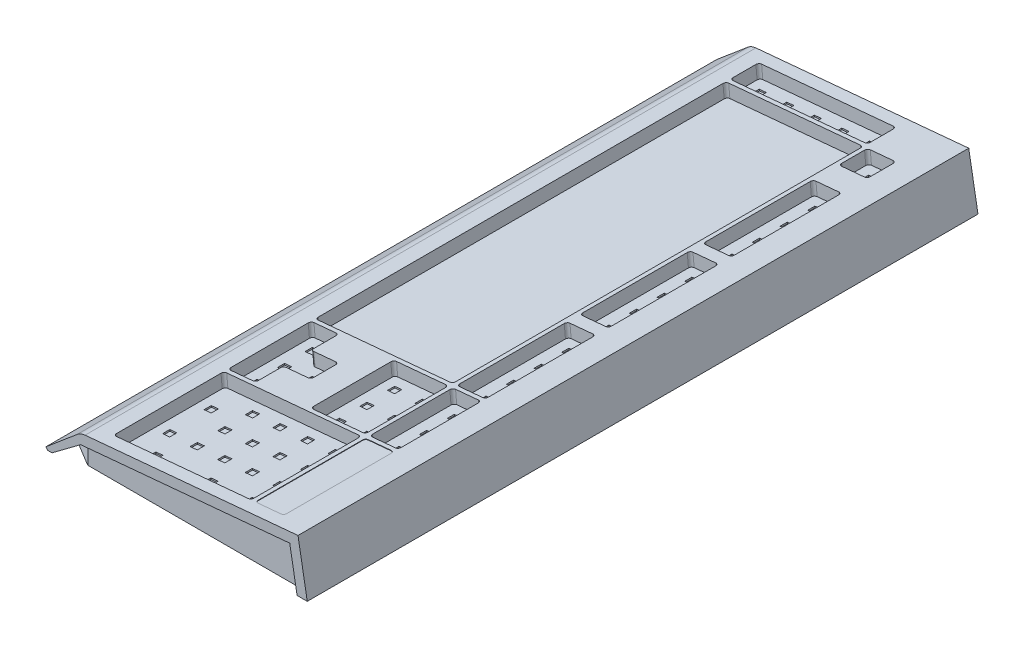
SolidWorks part; units mm, degrees
ref_plane "Front Plane" through (0, 0, 0) normal (0, 0, 1) x (1, 0, 0)
ref_plane "Top Plane" through (0, 0, 0) normal (0, 1, 0) x (1, 0, 0)
ref_plane "Right Plane" through (0, 0, 0) normal (1, 0, 0) x (0, 0, -1)
sketch "Sketch1" plane through (0, 0, 0) normal (0, 0, 1) x (1, 0, 0)
  line L0 (-76, 22) -> (76, 36)
  line L1 (-76, 0) -> (76, 0)
  line L2 (-76, 0) -> (-76, 22)
  line L4 (76, 0) -> (76, 36)
  point P2 (0, 29)
  dimension "D1" = 36
  dimension "D2" = 22
  dimension "D3" = 0
  dimension "D4" = 152
  dimension "D5" = 0
extrude "Boss-Extrude1" add sketch "Sketch1" along normal blind 459
sketch "Sketch4" plane through (0, 0, 459) normal (0, 0, 1) x (1, 0, 0)
  line L1 (70.2253, 28.4385) -> (75.3604, -0.684)
  line L2 (70.2253, 28.4385) -> (-76, 14.9704)
  line L3 (-76, 22) -> (-76, 0) construction
  line L4 (76, 36) -> (-76, 22) construction
  line L7 (76, 36) -> (-76, 22)
  line L8 (-76, 22) -> (-76, 14.9704)
  line L10 (76, 36) -> (82.4684, -0.684)
  line L11 (82.4684, -0.684) -> (75.3604, -0.684)
  dimension "D1" = 7
  dimension "D2" = 80
  dimension "D3" = 7
extrude "Boss-Extrude3" add sketch "Sketch4" along normal blind 5
sketch "Sketch6" plane through (0, 0, 0) normal (0, 0, -1) x (-1, 0, 0)
  line L0 (-69, 0) -> (-69, 28.3256)
  line L1 (76, 0) -> (-76, 0) construction
  line L2 (-69, 28.3256) -> (76, 14.9704)
  line L3 (76, 22) -> (76, 0) construction
  line L4 (76, 14.9704) -> (76, 22)
  line L5 (76, 22) -> (-76, 36)
  line L6 (-76, 36) -> (-76, 0)
  line L7 (-76, 0) -> (-69, 0)
  dimension "D1" = 7
  dimension "D2" = 7
extrude "Boss-Extrude5" add sketch "Sketch6" along normal blind 5
sketch "Sketch10" plane through (0, 0, 459) normal (0, 0, 1) x (1, 0, 0)
  line L0 (-76, 0) -> (-96, 0)
  line L1 (-96, 0) -> (-76, 14.9704)
  line L2 (-76, 14.9704) -> (-76, 0)
  dimension "D1" = 20
extrude "Boss-Extrude6" add sketch "Sketch10" against normal up to surface (459 mm away) up to face at (-3.5, 10.824, 0)
sketch "Sketch11" plane through (0, 0, 0) normal (0, -1, 0) x (1, 0, 0)
  line L0 (-76, -2.5) -> (-76, 461.5) construction
  line L1 (-76, -5) -> (-76, 0) construction
  line L2 (-76, 464) -> (-76, 459) construction
  line L3 (-76, 459) -> (-96, 447)
  line L4 (-96, 0) -> (-96, 459) construction
  line L5 (-96, 447) -> (-96, 459)
  line L6 (-96, 459) -> (-76, 459)
  line L7 (-76, 0) -> (-96, 12)
  line L9 (-96, 12) -> (-96, 0)
  line L10 (-96, 0) -> (-76, 0)
  dimension "D1" = 12
  dimension "D2" = 12
extrude "Cut-Extrude3" cut sketch "Sketch11" against normal up to next
sketch "Sketch12" plane through (0, 0, 464) normal (0, 0, 1) x (1, 0, 0)
  line L0 (-76, 14.9704) -> (-96, 0)
  line L1 (-96, 0) -> (-99, 0)
  line L2 (-99, 0) -> (-100.2034, 1.6077)
  line L3 (-100.2034, 1.6077) -> (-76, 22)
  line L4 (-76, 22) -> (-76, 14.9704)
  dimension "D1" = 3
  dimension "D2" = 3.3
extrude "Boss-Extrude7" add sketch "Sketch12" against normal up to surface (469 mm away) up to face at (23, 16.8827, -5)
sketch "Sketch19" plane through (0, 0, 459) normal (0, 0, -1) x (-1, 0, 0)
  line L3 (-82.4684, -0.684) -> (-75.3604, -0.684)
  line L4 (-76, 0) -> (-76, 36)
  line L5 (-76, 36) -> (-82.4684, -0.684)
  line L6 (-82.4684, -0.684) -> (-75.3604, -0.684)
  line L7 (-76, 0) -> (-76, 36)
  line L8 (-76, 36) -> (-82.4684, -0.684)
  line L11 (-75.3604, -0.684) -> (-75.2398, 0)
  line L12 (-75.3604, -0.684) -> (-75.2398, 0)
  line L13 (-75.2398, 0) -> (-76, 0)
  line L14 (-75.2398, 0) -> (-76, 0)
  dimension "D1" = 0
extrude "Boss-Extrude8" add sketch "Sketch19" along normal up to surface (464 mm away) up to face at (-17.467, 11.4337, -5)
sketch "Sketch20" plane through (0, 0, -5) normal (0, 0, -1) x (-1, 0, 0)
  line L0 (-69, 28.3256) -> (-73.9946, 0)
  line L2 (-76, 36) -> (-82.4684, -0.684) construction
  line L3 (-69, 28.3256) -> (-69, 0)
  line L4 (-75.2398, 0) -> (-69, 0) construction
  line L5 (-69, 0) -> (-69, 28.3256) construction
  line L6 (-69, 0) -> (-73.9946, 0)
extrude "Cut-Extrude10" cut sketch "Sketch20" against normal up to surface (5 mm away) up to face at (-3.5, 10.824, 0)
sketch "Sketch22" plane through (-2.6486, 28.7561, 0) normal (-0.0917, 0.9958, 0) x (0.9958, 0.0917, 0)
  line L0 (78.9815, -464) -> (-73.6619, -464) construction
  line L1 (57.9815, -378) -> (41.9815, -378)
  line L2 (59.9815, -380) -> (59.9815, -453)
  line L3 (57.9815, -455) -> (41.9815, -455)
  line L4 (39.9815, -380) -> (39.9815, -453)
  line L6 (78.9815, -464) -> (78.9815, 5) construction
  arc A0 (41.9815, -378) -> (39.9815, -380) centre (41.9815, -380) ccw
  arc A1 (41.9815, -455) -> (39.9815, -453) centre (41.9815, -453) cw
  arc A2 (59.9815, -453) -> (57.9815, -455) centre (57.9815, -453) cw
  arc A3 (57.9815, -378) -> (59.9815, -380) centre (57.9815, -380) cw
  point P10 (39.9815, -455)
  point P13 (59.9815, -455)
  point P16 (59.9815, -378)
  dimension "D4" = 2
  dimension "D1" = 9
  dimension "D2" = 77
  dimension "D3" = 20
  dimension "D5" = 19
extrude "Cut-Extrude12" cut sketch "Sketch22" against normal blind 0.3
sketch "Sketch23" plane through (-2.6486, 28.7561, 0) normal (-0.0917, 0.9958, 0) x (0.9958, 0.0917, 0)
  line L0 (78.9815, -464) -> (-73.6619, -464) construction
  line L2 (36.9815, -380) -> (36.9815, -453)
  line L3 (34.9815, -455) -> (-57.4385, -455)
  line L5 (39.9815, -380) -> (39.9815, -453) construction
  line L12 (-59.4385, -453) -> (-59.4385, -380)
  line L13 (-57.4385, -378) -> (34.9815, -378)
  line L14 (57.9815, -375) -> (41.9815, -375)
  line L15 (39.9815, -373) -> (39.9815, -319)
  line L16 (41.9815, -317) -> (57.9815, -317)
  line L17 (59.9815, -319) -> (59.9815, -373)
  line L19 (59.9815, -453) -> (59.9815, -380) construction
  line L20 (34.9815, -375) -> (0.5515, -375)
  line L21 (-59.4385, -373) -> (-59.4385, -319)
  line L22 (-57.4385, -317) -> (-42.1085, -317)
  line L23 (36.9815, -319) -> (36.9815, -373)
  line L24 (-40.1085, -319) -> (-40.1085, -334.3333)
  line L25 (-1.4485, -319) -> (-1.4485, -373)
  line L26 (-20.7785, -338.3333) -> (-20.7785, -353.6667)
  line L27 (0.5515, -317) -> (34.9815, -317)
  line L28 (-42.1085, -375) -> (-57.4385, -375)
  line L29 (-22.7785, -336.3333) -> (-38.1085, -336.3333)
  line L30 (-22.7785, -355.6667) -> (-38.1085, -355.6667)
  line L31 (-40.1085, -357.6667) -> (-40.1085, -373)
  line L36 (39.9815, -373) -> (39.9815, 5) construction
  line L37 (-73.6619, 5) -> (78.9815, 5) construction
  line L38 (59.9815, -319) -> (59.9815, 5) construction
  line L39 (57.9815, -314) -> (41.9815, -314)
  line L40 (39.9815, -312) -> (39.9815, -239)
  line L41 (41.9815, -237) -> (57.9815, -237)
  line L42 (59.9815, -239) -> (59.9815, -312)
  line L43 (57.9815, -228) -> (41.9815, -228)
  line L44 (39.9815, -226) -> (39.9815, -153)
  line L45 (41.9815, -151) -> (57.9815, -151)
  line L46 (59.9815, -153) -> (59.9815, -226)
  line L47 (57.9815, -142) -> (41.9815, -142)
  line L48 (39.9815, -140) -> (39.9815, -67)
  line L49 (41.9815, -65) -> (57.9815, -65)
  line L50 (59.9815, -67) -> (59.9815, -140)
  line L51 (57.9815, -27) -> (41.9815, -27)
  line L52 (39.9815, -29) -> (39.9815, -45)
  line L53 (41.9815, -47) -> (57.9815, -47)
  line L54 (59.9815, -45) -> (59.9815, -29)
  line L55 (36.9815, -319) -> (36.9815, 5) construction
  line L56 (-59.4385, -319) -> (-59.4385, 5) construction
  line L57 (34.9815, -4) -> (-57.4385, -4)
  line L58 (-59.4385, -6) -> (-59.4385, -22)
  line L59 (-57.4385, -24) -> (34.9815, -24)
  line L60 (36.9815, -22) -> (36.9815, -6)
  line L61 (34.9815, -27) -> (-57.4385, -27)
  line L62 (-59.4385, -29) -> (-59.4385, -312)
  line L63 (-57.4385, -314) -> (34.9815, -314)
  line L64 (36.9815, -312) -> (36.9815, -29)
  arc A4 (-59.4385, -380) -> (-57.4385, -378) centre (-57.4385, -380) cw
  arc A5 (-57.4385, -455) -> (-59.4385, -453) centre (-57.4385, -453) cw
  arc A6 (36.9815, -453) -> (34.9815, -455) centre (34.9815, -453) cw
  arc A7 (36.9815, -380) -> (34.9815, -378) centre (34.9815, -380) ccw
  arc A8 (39.9815, -319) -> (41.9815, -317) centre (41.9815, -319) cw
  arc A9 (41.9815, -375) -> (39.9815, -373) centre (41.9815, -373) cw
  arc A10 (57.9815, -375) -> (59.9815, -373) centre (57.9815, -373) ccw
  arc A11 (57.9815, -317) -> (59.9815, -319) centre (57.9815, -319) cw
  arc A12 (-40.1085, -373) -> (-42.1085, -375) centre (-42.1085, -373) cw
  arc A13 (-57.4385, -375) -> (-59.4385, -373) centre (-57.4385, -373) cw
  arc A14 (-59.4385, -319) -> (-57.4385, -317) centre (-57.4385, -319) cw
  arc A15 (-40.1085, -319) -> (-42.1085, -317) centre (-42.1085, -319) ccw
  arc A16 (-38.1085, -336.3333) -> (-40.1085, -334.3333) centre (-38.1085, -334.3333) cw
  arc A17 (-38.1085, -355.6667) -> (-40.1085, -357.6667) centre (-38.1085, -357.6667) ccw
  arc A18 (-22.7785, -355.6667) -> (-20.7785, -353.6667) centre (-22.7785, -353.6667) ccw
  arc A19 (-22.7785, -336.3333) -> (-20.7785, -338.3333) centre (-22.7785, -338.3333) cw
  arc A20 (-1.4485, -319) -> (0.5515, -317) centre (0.5515, -319) cw
  arc A21 (-1.4485, -373) -> (0.5515, -375) centre (0.5515, -373) ccw
  arc A22 (34.9815, -375) -> (36.9815, -373) centre (34.9815, -373) ccw
  arc A23 (34.9815, -317) -> (36.9815, -319) centre (34.9815, -319) cw
  arc A24 (57.9815, -314) -> (59.9815, -312) centre (57.9815, -312) ccw
  arc A25 (41.9815, -314) -> (39.9815, -312) centre (41.9815, -312) cw
  arc A26 (39.9815, -239) -> (41.9815, -237) centre (41.9815, -239) cw
  arc A27 (57.9815, -237) -> (59.9815, -239) centre (57.9815, -239) cw
  arc A28 (57.9815, -228) -> (59.9815, -226) centre (57.9815, -226) ccw
  arc A29 (41.9815, -228) -> (39.9815, -226) centre (41.9815, -226) cw
  arc A30 (39.9815, -153) -> (41.9815, -151) centre (41.9815, -153) cw
  arc A31 (57.9815, -151) -> (59.9815, -153) centre (57.9815, -153) cw
  arc A32 (39.9815, -67) -> (41.9815, -65) centre (41.9815, -67) cw
  arc A33 (41.9815, -142) -> (39.9815, -140) centre (41.9815, -140) cw
  arc A34 (57.9815, -142) -> (59.9815, -140) centre (57.9815, -140) ccw
  arc A35 (57.9815, -65) -> (59.9815, -67) centre (57.9815, -67) cw
  arc A36 (41.9815, -27) -> (39.9815, -29) centre (41.9815, -29) ccw
  arc A37 (39.9815, -45) -> (41.9815, -47) centre (41.9815, -45) ccw
  arc A38 (57.9815, -47) -> (59.9815, -45) centre (57.9815, -45) ccw
  arc A39 (57.9815, -27) -> (59.9815, -29) centre (57.9815, -29) cw
  arc A40 (-57.4385, -4) -> (-59.4385, -6) centre (-57.4385, -6) ccw
  arc A41 (-59.4385, -22) -> (-57.4385, -24) centre (-57.4385, -22) ccw
  arc A42 (34.9815, -24) -> (36.9815, -22) centre (34.9815, -22) ccw
  arc A43 (34.9815, -4) -> (36.9815, -6) centre (34.9815, -6) cw
  arc A44 (-57.4385, -27) -> (-59.4385, -29) centre (-57.4385, -29) ccw
  arc A45 (-59.4385, -312) -> (-57.4385, -314) centre (-57.4385, -312) ccw
  arc A46 (34.9815, -314) -> (36.9815, -312) centre (34.9815, -312) ccw
  arc A47 (34.9815, -27) -> (36.9815, -29) centre (34.9815, -29) cw
  point P11 (-59.4385, -455)
  point P15 (36.9815, -455)
  point P16 (36.9815, -455)
  point P49 (-40.1085, -375)
  point P60 (-40.1085, -355.6667)
  point P67 (-1.4485, -317)
  point P92 (59.9815, -314)
  point P95 (39.9815, -314)
  point P98 (39.9815, -237)
  point P101 (59.9815, -237)
  point P104 (59.9815, -228)
  point P107 (39.9815, -228)
  point P110 (39.9815, -151)
  point P113 (59.9815, -151)
  point P116 (39.9815, -65)
  point P119 (39.9815, -142)
  point P122 (59.9815, -142)
  point P125 (59.9815, -65)
  point P132 (39.9815, -27)
  point P135 (39.9815, -47)
  point P138 (59.9815, -47)
  point P141 (59.9815, -27)
  point P150 (-59.4385, -4)
  point P153 (-59.4385, -24)
  point P156 (36.9815, -24)
  point P159 (36.9815, -4)
  point P166 (-59.4385, -27)
  point P169 (-59.4385, -314)
  point P172 (36.9815, -314)
  point P175 (36.9815, -27)
  dimension "D5" = 2
  dimension "D10" = 2
  dimension "D18" = 2
  dimension "D25" = 2
  dimension "D28" = 2
  dimension "D31" = 2
  dimension "D34" = 2
  dimension "D3" = 77
  dimension "D4" = 3
  dimension "D6" = 3
  dimension "D7" = 58
  dimension "D8" = 0
  dimension "D9" = 20
  dimension "D11" = 3
  dimension "D12" = 96.42
  dimension "D13" = 38.43
  dimension "D14" = 19.33
  dimension "D15" = 19.33
  dimension "D16" = 19.3333
  dimension "D17" = 19.3333
  dimension "D19" = 3
  dimension "D20" = 77
  dimension "D21" = 9
  dimension "D22" = 77
  dimension "D23" = 9
  dimension "D24" = 77
  dimension "D26" = 18
  dimension "D27" = 20
  dimension "D29" = 3
  dimension "D30" = 20
  dimension "D32" = 3
  dimension "D33" = 3
  dimension "D35" = 9
  dimension "D36" = 96.42
extrude "Cut-Extrude13" cut sketch "Sketch23" against normal blind 9
fillet "Fillet5" radius 10 1 edges at (-76, 22, 229.5)
sketch "Sketch78" plane through (-1.8231, 19.794, 0) normal (-0.0917, 0.9958, 0) x (0.9958, 0.0917, 0)
  line L0 (-20.7785, -346) -> (-59.4385, -346) construction
  line L1 (-20.7785, -353.6667) -> (-20.7785, -338.3333) construction
  line L2 (-59.4385, -319) -> (-59.4385, -373) construction
  line L3 (-49.7735, -317) -> (-49.7735, -375) construction
  line L4 (-42.1085, -317) -> (-57.4385, -317) construction
  line L5 (-57.4385, -375) -> (-42.1085, -375) construction
  line L6 (-40.1085, -326.6667) -> (-59.4385, -326.6667) construction
  line L7 (-40.1085, -334.3333) -> (-40.1085, -319) construction
  line L8 (-40.1085, -365.3333) -> (-59.4385, -365.3333) construction
  line L9 (-40.1085, -373) -> (-40.1085, -357.6667) construction
  line L10 (-30.4435, -336.3333) -> (-30.4435, -355.6667) construction
  line L11 (-22.7785, -336.3333) -> (-38.1085, -336.3333) construction
  line L12 (-38.1085, -355.6667) -> (-22.7785, -355.6667) construction
  line L13 (36.9815, -346) -> (-1.4485, -346) construction
  line L14 (-32.9435, -348.5) -> (-27.9435, -348.5)
  line L15 (-32.9435, -348.5) -> (-32.9435, -343.5)
  line L16 (-32.9435, -343.5) -> (-27.9435, -343.5)
  line L17 (-27.9435, -348.5) -> (-27.9435, -343.5)
  line L18 (-32.9435, -348.5) -> (-27.9435, -343.5) construction
  line L19 (-32.9435, -343.5) -> (-27.9435, -348.5) construction
  line L20 (-52.2735, -329.1667) -> (-47.2735, -329.1667)
  line L21 (-52.2735, -329.1667) -> (-52.2735, -324.1667)
  line L22 (-52.2735, -324.1667) -> (-47.2735, -324.1667)
  line L23 (-47.2735, -329.1667) -> (-47.2735, -324.1667)
  line L24 (-52.2735, -329.1667) -> (-47.2735, -324.1667) construction
  line L25 (-52.2735, -324.1667) -> (-47.2735, -329.1667) construction
  line L26 (-52.2735, -348.5) -> (-47.2735, -348.5)
  line L27 (-52.2735, -348.5) -> (-52.2735, -343.5)
  line L28 (-52.2735, -343.5) -> (-47.2735, -343.5)
  line L29 (-47.2735, -348.5) -> (-47.2735, -343.5)
  line L30 (-52.2735, -348.5) -> (-47.2735, -343.5) construction
  line L31 (-52.2735, -343.5) -> (-47.2735, -348.5) construction
  line L32 (-52.2735, -367.8333) -> (-47.2735, -367.8333)
  line L33 (-52.2735, -367.8333) -> (-52.2735, -362.8333)
  line L34 (-52.2735, -362.8333) -> (-47.2735, -362.8333)
  line L35 (-47.2735, -367.8333) -> (-47.2735, -362.8333)
  line L36 (-52.2735, -367.8333) -> (-47.2735, -362.8333) construction
  line L37 (-52.2735, -362.8333) -> (-47.2735, -367.8333) construction
  line L38 (36.9815, -373) -> (36.9815, -319) construction
  line L39 (-1.4485, -319) -> (-1.4485, -373) construction
  line L40 (36.9815, -326.6667) -> (-1.4485, -326.6667) construction
  line L41 (36.9815, -365.3333) -> (-1.4485, -365.3333) construction
  line L42 (-59.4385, -380) -> (-59.4385, -453) construction
  line L43 (34.9815, -317) -> (0.5515, -317) construction
  line L44 (0.5515, -375) -> (34.9815, -375) construction
  line L45 (49.9815, -317) -> (49.9815, -375) construction
  line L46 (57.9815, -317) -> (41.9815, -317) construction
  line L47 (27.4315, -317) -> (27.4315, -375) construction
  line L48 (8.1015, -317) -> (8.1015, -375) construction
  line L49 (41.9815, -375) -> (57.9815, -375) construction
  line L50 (24.9315, -348.5) -> (29.9315, -348.5)
  line L51 (24.9315, -348.5) -> (24.9315, -343.5)
  line L52 (24.9315, -343.5) -> (29.9315, -343.5)
  line L53 (29.9315, -348.5) -> (29.9315, -343.5)
  line L54 (24.9315, -348.5) -> (29.9315, -343.5) construction
  line L55 (24.9315, -343.5) -> (29.9315, -348.5) construction
  line L56 (5.6015, -348.5) -> (10.6015, -348.5)
  line L57 (5.6015, -348.5) -> (5.6015, -343.5)
  line L58 (5.6015, -343.5) -> (10.6015, -343.5)
  line L59 (10.6015, -348.5) -> (10.6015, -343.5)
  line L60 (5.6015, -348.5) -> (10.6015, -343.5) construction
  line L61 (5.6015, -343.5) -> (10.6015, -348.5) construction
  line L62 (24.9315, -367.8333) -> (29.9315, -367.8333)
  line L63 (24.9315, -367.8333) -> (24.9315, -362.8333)
  line L64 (24.9315, -362.8333) -> (29.9315, -362.8333)
  line L65 (29.9315, -367.8333) -> (29.9315, -362.8333)
  line L66 (24.9315, -367.8333) -> (29.9315, -362.8333) construction
  line L67 (24.9315, -362.8333) -> (29.9315, -367.8333) construction
  line L68 (24.9315, -329.1667) -> (29.9315, -329.1667)
  line L69 (24.9315, -329.1667) -> (24.9315, -324.1667)
  line L70 (24.9315, -324.1667) -> (29.9315, -324.1667)
  line L71 (29.9315, -329.1667) -> (29.9315, -324.1667)
  line L72 (24.9315, -329.1667) -> (29.9315, -324.1667) construction
  line L73 (24.9315, -324.1667) -> (29.9315, -329.1667) construction
  line L74 (5.6015, -329.1667) -> (10.6015, -329.1667)
  line L75 (5.6015, -329.1667) -> (5.6015, -324.1667)
  line L76 (5.6015, -324.1667) -> (10.6015, -324.1667)
  line L77 (10.6015, -329.1667) -> (10.6015, -324.1667)
  line L78 (5.6015, -329.1667) -> (10.6015, -324.1667) construction
  line L79 (5.6015, -324.1667) -> (10.6015, -329.1667) construction
  line L80 (5.6015, -367.8333) -> (10.6015, -367.8333)
  line L81 (5.6015, -367.8333) -> (5.6015, -362.8333)
  line L82 (5.6015, -362.8333) -> (10.6015, -362.8333)
  line L83 (10.6015, -367.8333) -> (10.6015, -362.8333)
  line L84 (5.6015, -367.8333) -> (10.6015, -362.8333) construction
  line L85 (5.6015, -362.8333) -> (10.6015, -367.8333) construction
  line L86 (59.9815, -346) -> (39.9815, -346) construction
  line L87 (59.9815, -373) -> (59.9815, -319) construction
  line L88 (39.9815, -319) -> (39.9815, -373) construction
  line L89 (59.9815, -326.6667) -> (39.9815, -326.6667) construction
  line L90 (59.9815, -365.3333) -> (39.9815, -365.3333) construction
  line L91 (59.9815, -37) -> (39.9815, -37) construction
  line L92 (47.4815, -329.1667) -> (52.4815, -329.1667)
  line L93 (47.4815, -329.1667) -> (47.4815, -324.1667)
  line L94 (47.4815, -324.1667) -> (52.4815, -324.1667)
  line L95 (52.4815, -329.1667) -> (52.4815, -324.1667)
  line L96 (47.4815, -329.1667) -> (52.4815, -324.1667) construction
  line L97 (47.4815, -324.1667) -> (52.4815, -329.1667) construction
  line L98 (47.4815, -348.5) -> (52.4815, -348.5)
  line L99 (47.4815, -348.5) -> (47.4815, -343.5)
  line L100 (47.4815, -343.5) -> (52.4815, -343.5)
  line L101 (52.4815, -348.5) -> (52.4815, -343.5)
  line L102 (47.4815, -348.5) -> (52.4815, -343.5) construction
  line L103 (47.4815, -343.5) -> (52.4815, -348.5) construction
  line L104 (47.4815, -367.8333) -> (52.4815, -367.8333)
  line L105 (47.4815, -367.8333) -> (47.4815, -362.8333)
  line L106 (47.4815, -362.8333) -> (52.4815, -362.8333)
  line L107 (52.4815, -367.8333) -> (52.4815, -362.8333)
  line L108 (47.4815, -367.8333) -> (52.4815, -362.8333) construction
  line L109 (47.4815, -362.8333) -> (52.4815, -367.8333) construction
  line L110 (59.9815, -45) -> (59.9815, -29) construction
  line L111 (39.9815, -29) -> (39.9815, -45) construction
  line L112 (49.9815, -27) -> (49.9815, -47) construction
  line L113 (57.9815, -27) -> (41.9815, -27) construction
  line L114 (41.9815, -47) -> (57.9815, -47) construction
  line L115 (36.9815, -14) -> (-59.4385, -14) construction
  line L116 (47.4815, -39.5) -> (52.4815, -39.5)
  line L117 (47.4815, -39.5) -> (47.4815, -34.5)
  line L118 (47.4815, -34.5) -> (52.4815, -34.5)
  line L119 (52.4815, -39.5) -> (52.4815, -34.5)
  line L120 (47.4815, -39.5) -> (52.4815, -34.5) construction
  line L121 (47.4815, -34.5) -> (52.4815, -39.5) construction
  line L122 (36.9815, -22) -> (36.9815, -6) construction
  line L123 (-59.4385, -6) -> (-59.4385, -22) construction
  line L124 (-11.2285, -4) -> (-11.2285, -24) construction
  line L125 (34.9815, -4) -> (-57.4385, -4) construction
  line L126 (-57.4385, -24) -> (34.9815, -24) construction
  line L127 (27.4315, -4) -> (27.4315, -24) construction
  line L128 (8.1015, -4) -> (8.1015, -24) construction
  line L129 (-30.5585, -4) -> (-30.5585, -24) construction
  line L130 (-49.8885, -4) -> (-49.8885, -24) construction
  line L131 (49.9815, -65) -> (49.9815, -314) construction
  line L132 (24.9315, -16.5) -> (29.9315, -16.5)
  line L133 (24.9315, -16.5) -> (24.9315, -11.5)
  line L134 (24.9315, -11.5) -> (29.9315, -11.5)
  line L135 (29.9315, -16.5) -> (29.9315, -11.5)
  line L136 (24.9315, -16.5) -> (29.9315, -11.5) construction
  line L137 (24.9315, -11.5) -> (29.9315, -16.5) construction
  line L138 (5.6015, -16.5) -> (10.6015, -16.5)
  line L139 (5.6015, -16.5) -> (5.6015, -11.5)
  line L140 (5.6015, -11.5) -> (10.6015, -11.5)
  line L141 (10.6015, -16.5) -> (10.6015, -11.5)
  line L142 (5.6015, -16.5) -> (10.6015, -11.5) construction
  line L143 (5.6015, -11.5) -> (10.6015, -16.5) construction
  line L144 (-13.7285, -16.5) -> (-8.7285, -16.5)
  line L145 (-13.7285, -16.5) -> (-13.7285, -11.5)
  line L146 (-13.7285, -11.5) -> (-8.7285, -11.5)
  line L147 (-8.7285, -16.5) -> (-8.7285, -11.5)
  line L148 (-13.7285, -16.5) -> (-8.7285, -11.5) construction
  line L149 (-13.7285, -11.5) -> (-8.7285, -16.5) construction
  line L150 (-33.0585, -16.5) -> (-28.0585, -16.5)
  line L151 (-33.0585, -16.5) -> (-33.0585, -11.5)
  line L152 (-33.0585, -11.5) -> (-28.0585, -11.5)
  line L153 (-28.0585, -16.5) -> (-28.0585, -11.5)
  line L154 (-33.0585, -16.5) -> (-28.0585, -11.5) construction
  line L155 (-33.0585, -11.5) -> (-28.0585, -16.5) construction
  line L156 (-52.3885, -16.5) -> (-47.3885, -16.5)
  line L157 (-52.3885, -16.5) -> (-52.3885, -11.5)
  line L158 (-52.3885, -11.5) -> (-47.3885, -11.5)
  line L159 (-47.3885, -16.5) -> (-47.3885, -11.5)
  line L160 (-52.3885, -16.5) -> (-47.3885, -11.5) construction
  line L161 (-52.3885, -11.5) -> (-47.3885, -16.5) construction
  line L162 (57.9815, -65) -> (41.9815, -65) construction
  line L163 (41.9815, -314) -> (57.9815, -314) construction
  line L164 (59.9815, -74.505) -> (39.9815, -74.505) construction
  line L165 (59.9815, -140) -> (59.9815, -67) construction
  line L166 (39.9815, -67) -> (39.9815, -140) construction
  line L167 (59.9815, -93.835) -> (39.9815, -93.835) construction
  line L168 (59.9815, -113.165) -> (39.9815, -113.165) construction
  line L169 (59.9815, -132.495) -> (39.9815, -132.495) construction
  line L170 (-1.5635, -455) -> (-1.5635, -378) construction
  line L171 (-13.7285, -428.67) -> (-8.7285, -428.67)
  line L172 (-13.7285, -428.67) -> (-13.7285, -423.67)
  line L173 (-13.7285, -423.67) -> (-8.7285, -423.67)
  line L174 (-8.7285, -428.67) -> (-8.7285, -423.67)
  line L175 (69.2142, -146.5) -> (26.7315, -146.5) construction
  line L176 (47.4815, -72.005) -> (52.4815, -72.005)
  line L177 (47.4815, -72.005) -> (47.4815, -77.005)
  line L178 (47.4815, -77.005) -> (52.4815, -77.005)
  line L179 (52.4815, -72.005) -> (52.4815, -77.005)
  line L180 (47.4815, -72.005) -> (52.4815, -77.005) construction
  line L181 (47.4815, -77.005) -> (52.4815, -72.005) construction
  line L182 (47.4815, -91.335) -> (52.4815, -91.335)
  line L183 (47.4815, -91.335) -> (47.4815, -96.335)
  line L184 (47.4815, -96.335) -> (52.4815, -96.335)
  line L185 (52.4815, -91.335) -> (52.4815, -96.335)
  line L186 (47.4815, -91.335) -> (52.4815, -96.335) construction
  line L187 (47.4815, -96.335) -> (52.4815, -91.335) construction
  line L188 (47.4815, -110.665) -> (52.4815, -110.665)
  line L189 (47.4815, -110.665) -> (47.4815, -115.665)
  line L190 (47.4815, -115.665) -> (52.4815, -115.665)
  line L191 (52.4815, -110.665) -> (52.4815, -115.665)
  line L192 (47.4815, -110.665) -> (52.4815, -115.665) construction
  line L193 (47.4815, -115.665) -> (52.4815, -110.665) construction
  line L194 (47.4815, -129.995) -> (52.4815, -129.995)
  line L195 (47.4815, -129.995) -> (47.4815, -134.995)
  line L196 (47.4815, -134.995) -> (52.4815, -134.995)
  line L197 (52.4815, -129.995) -> (52.4815, -134.995)
  line L198 (47.4815, -129.995) -> (52.4815, -134.995) construction
  line L199 (47.4815, -134.995) -> (52.4815, -129.995) construction
  line L200 (67.6137, -232.5) -> (26.7315, -232.5) construction
  line L201 (41.9815, -228) -> (57.9815, -228) construction
  line L202 (-13.7285, -428.67) -> (-8.7285, -423.67) construction
  line L203 (-13.7285, -423.67) -> (-8.7285, -428.67) construction
  line L204 (41.9815, -142) -> (57.9815, -142) construction
  line L205 (52.4815, -163.005) -> (52.4815, -158.005)
  line L206 (47.4815, -158.005) -> (52.4815, -158.005)
  line L207 (47.4815, -163.005) -> (47.4815, -158.005)
  line L208 (47.4815, -163.005) -> (52.4815, -163.005)
  line L209 (52.4815, -182.335) -> (52.4815, -177.335)
  line L210 (47.4815, -177.335) -> (52.4815, -177.335)
  line L211 (47.4815, -182.335) -> (47.4815, -177.335)
  line L212 (47.4815, -182.335) -> (52.4815, -182.335)
  line L213 (47.4815, -196.665) -> (52.4815, -196.665)
  line L214 (47.4815, -201.665) -> (47.4815, -196.665)
  line L215 (47.4815, -201.665) -> (52.4815, -201.665)
  line L216 (52.4815, -201.665) -> (52.4815, -196.665)
  line L217 (52.4815, -220.995) -> (52.4815, -215.995)
  line L218 (47.4815, -220.995) -> (52.4815, -220.995)
  line L219 (47.4815, -220.995) -> (47.4815, -215.995)
  line L220 (47.4815, -215.995) -> (52.4815, -215.995)
  line L221 (47.4815, -244.005) -> (52.4815, -244.005)
  line L222 (47.4815, -244.005) -> (47.4815, -249.005)
  line L223 (47.4815, -249.005) -> (52.4815, -249.005)
  line L224 (52.4815, -244.005) -> (52.4815, -249.005)
  line L225 (47.4815, -263.335) -> (47.4815, -268.335)
  line L226 (47.4815, -263.335) -> (52.4815, -263.335)
  line L227 (52.4815, -263.335) -> (52.4815, -268.335)
  line L228 (47.4815, -268.335) -> (52.4815, -268.335)
  line L229 (47.4815, -282.665) -> (52.4815, -282.665)
  line L230 (47.4815, -282.665) -> (47.4815, -287.665)
  line L231 (47.4815, -287.665) -> (52.4815, -287.665)
  line L232 (52.4815, -282.665) -> (52.4815, -287.665)
  line L233 (47.4815, -301.995) -> (52.4815, -301.995)
  line L234 (47.4815, -301.995) -> (47.4815, -306.995)
  line L235 (47.4815, -306.995) -> (52.4815, -306.995)
  line L236 (52.4815, -301.995) -> (52.4815, -306.995)
  line L237 (27.4315, -455) -> (27.4315, -378) construction
  line L238 (-57.4385, -455) -> (34.9815, -455) construction
  line L239 (34.9815, -378) -> (-57.4385, -378) construction
  line L240 (8.1015, -455) -> (8.1015, -378) construction
  line L241 (-11.2285, -455) -> (-11.2285, -378) construction
  line L242 (-30.5585, -455) -> (-30.5585, -378) construction
  line L243 (-49.8885, -455) -> (-49.8885, -378) construction
  line L244 (36.9815, -387.51) -> (-59.4385, -387.51) construction
  line L245 (-13.7285, -409.34) -> (-8.7285, -409.34)
  line L246 (-13.7285, -409.34) -> (-13.7285, -404.34)
  line L247 (-13.7285, -404.34) -> (-8.7285, -404.34)
  line L248 (-8.7285, -409.34) -> (-8.7285, -404.34)
  line L249 (36.9815, -453) -> (36.9815, -380) construction
  line L250 (36.9815, -406.84) -> (-59.4385, -406.84) construction
  line L251 (36.9815, -426.17) -> (-59.4385, -426.17) construction
  line L252 (36.9815, -445.5) -> (-59.4385, -445.5) construction
  line L253 (-13.7285, -409.34) -> (-8.7285, -404.34) construction
  line L254 (24.9315, -390.01) -> (29.9315, -390.01)
  line L255 (24.9315, -390.01) -> (24.9315, -385.01)
  line L256 (24.9315, -385.01) -> (29.9315, -385.01)
  line L257 (29.9315, -390.01) -> (29.9315, -385.01)
  line L258 (24.9315, -390.01) -> (29.9315, -385.01) construction
  line L259 (24.9315, -385.01) -> (29.9315, -390.01) construction
  line L260 (24.9315, -409.34) -> (29.9315, -409.34)
  line L261 (24.9315, -409.34) -> (24.9315, -404.34)
  line L262 (24.9315, -404.34) -> (29.9315, -404.34)
  line L263 (29.9315, -409.34) -> (29.9315, -404.34)
  line L264 (24.9315, -409.34) -> (29.9315, -404.34) construction
  line L265 (24.9315, -404.34) -> (29.9315, -409.34) construction
  line L266 (24.9315, -428.67) -> (29.9315, -428.67)
  line L267 (24.9315, -428.67) -> (24.9315, -423.67)
  line L268 (24.9315, -423.67) -> (29.9315, -423.67)
  line L269 (29.9315, -428.67) -> (29.9315, -423.67)
  line L270 (24.9315, -428.67) -> (29.9315, -423.67) construction
  line L271 (24.9315, -423.67) -> (29.9315, -428.67) construction
  line L272 (24.9315, -448) -> (29.9315, -448)
  line L273 (24.9315, -448) -> (24.9315, -443)
  line L274 (24.9315, -443) -> (29.9315, -443)
  line L275 (29.9315, -448) -> (29.9315, -443)
  line L276 (24.9315, -448) -> (29.9315, -443) construction
  line L277 (24.9315, -443) -> (29.9315, -448) construction
  line L278 (-13.7285, -404.34) -> (-8.7285, -409.34) construction
  line L279 (-13.7285, -390.01) -> (-8.7285, -390.01)
  line L280 (-13.7285, -390.01) -> (-13.7285, -385.01)
  line L281 (-13.7285, -385.01) -> (-8.7285, -385.01)
  line L282 (-8.7285, -390.01) -> (-8.7285, -385.01)
  line L283 (-13.7285, -390.01) -> (-8.7285, -385.01) construction
  line L284 (-13.7285, -385.01) -> (-8.7285, -390.01) construction
  line L285 (5.6015, -390.01) -> (10.6015, -390.01)
  line L286 (5.6015, -390.01) -> (5.6015, -385.01)
  line L287 (5.6015, -385.01) -> (10.6015, -385.01)
  line L288 (10.6015, -390.01) -> (10.6015, -385.01)
  line L289 (5.6015, -390.01) -> (10.6015, -385.01) construction
  line L290 (5.6015, -385.01) -> (10.6015, -390.01) construction
  line L291 (5.6015, -409.34) -> (10.6015, -409.34)
  line L292 (5.6015, -409.34) -> (5.6015, -404.34)
  line L293 (5.6015, -404.34) -> (10.6015, -404.34)
  line L294 (10.6015, -409.34) -> (10.6015, -404.34)
  line L295 (5.6015, -409.34) -> (10.6015, -404.34) construction
  line L296 (5.6015, -404.34) -> (10.6015, -409.34) construction
  line L297 (5.6015, -428.67) -> (10.6015, -428.67)
  line L298 (5.6015, -428.67) -> (5.6015, -423.67)
  line L299 (5.6015, -423.67) -> (10.6015, -423.67)
  line L300 (10.6015, -428.67) -> (10.6015, -423.67)
  line L301 (5.6015, -428.67) -> (10.6015, -423.67) construction
  line L302 (5.6015, -423.67) -> (10.6015, -428.67) construction
  line L303 (-40.2235, -378) -> (-40.2235, -455) construction
  line L304 (0.9365, -448) -> (-4.0635, -448)
  line L305 (0.9365, -448) -> (0.9365, -443)
  line L306 (0.9365, -443) -> (-4.0635, -443)
  line L307 (-4.0635, -448) -> (-4.0635, -443)
  line L308 (0.9365, -448) -> (-4.0635, -443) construction
  line L309 (0.9365, -443) -> (-4.0635, -448) construction
  line L310 (-33.0585, -390.01) -> (-28.0585, -390.01)
  line L311 (-33.0585, -390.01) -> (-33.0585, -385.01)
  line L312 (-33.0585, -385.01) -> (-28.0585, -385.01)
  line L313 (-28.0585, -390.01) -> (-28.0585, -385.01)
  line L314 (-33.0585, -390.01) -> (-28.0585, -385.01) construction
  line L315 (-33.0585, -385.01) -> (-28.0585, -390.01) construction
  line L316 (-33.0585, -409.34) -> (-28.0585, -409.34)
  line L317 (-33.0585, -409.34) -> (-33.0585, -404.34)
  line L318 (-33.0585, -404.34) -> (-28.0585, -404.34)
  line L319 (-28.0585, -409.34) -> (-28.0585, -404.34)
  line L320 (-33.0585, -409.34) -> (-28.0585, -404.34) construction
  line L321 (-33.0585, -404.34) -> (-28.0585, -409.34) construction
  line L322 (-33.0585, -428.67) -> (-28.0585, -428.67)
  line L323 (-33.0585, -428.67) -> (-33.0585, -423.67)
  line L324 (-33.0585, -423.67) -> (-28.0585, -423.67)
  line L325 (-28.0585, -428.67) -> (-28.0585, -423.67)
  line L326 (-33.0585, -428.67) -> (-28.0585, -423.67) construction
  line L327 (-33.0585, -423.67) -> (-28.0585, -428.67) construction
  line L328 (-30.5585, -397.175) -> (-59.4385, -397.175) construction
  line L329 (-42.7235, -448) -> (-37.7235, -448)
  line L330 (-42.7235, -448) -> (-42.7235, -443)
  line L331 (-42.7235, -443) -> (-37.7235, -443)
  line L332 (-37.7235, -448) -> (-37.7235, -443)
  line L333 (-42.7235, -448) -> (-37.7235, -443) construction
  line L334 (-42.7235, -443) -> (-37.7235, -448) construction
  line L335 (-52.3885, -428.67) -> (-47.3885, -428.67)
  line L336 (-52.3885, -428.67) -> (-52.3885, -423.67)
  line L337 (-52.3885, -423.67) -> (-47.3885, -423.67)
  line L338 (-47.3885, -428.67) -> (-47.3885, -423.67)
  line L339 (-52.3885, -428.67) -> (-47.3885, -423.67) construction
  line L340 (-52.3885, -423.67) -> (-47.3885, -428.67) construction
  line L341 (-52.3885, -399.675) -> (-47.3885, -399.675)
  line L342 (-52.3885, -399.675) -> (-52.3885, -394.675)
  line L343 (-52.3885, -394.675) -> (-47.3885, -394.675)
  line L344 (-47.3885, -399.675) -> (-47.3885, -394.675)
  line L345 (-52.3885, -399.675) -> (-47.3885, -394.675) construction
  line L346 (-52.3885, -394.675) -> (-47.3885, -399.675) construction
  point P26 (-30.4435, -346)
  point P31 (-49.7735, -326.6667)
  point P36 (-49.7735, -346)
  point P41 (-49.7735, -365.3333)
  point P66 (27.4315, -346)
  point P71 (8.1015, -346)
  point P76 (27.4315, -365.3333)
  point P81 (27.4315, -326.6667)
  point P86 (8.1015, -326.6667)
  point P91 (8.1015, -365.3333)
  point P112 (49.9815, -326.6667)
  point P117 (49.9815, -346)
  point P122 (49.9815, -365.3333)
  point P139 (49.9815, -37)
  point P164 (27.4315, -14)
  point P169 (8.1015, -14)
  point P174 (-11.2285, -14)
  point P179 (-30.5585, -14)
  point P184 (-49.8885, -14)
  point P207 (49.9815, -93.835)
  point P209 (49.9815, -74.505)
  point P217 (49.9815, -113.165)
  point P222 (49.9815, -132.495)
  point P289 (27.4315, -406.84)
  point P293 (27.4315, -387.51)
  point P299 (27.4315, -426.17)
  point P304 (27.4315, -445.5)
  point P309 (-11.2285, -406.84)
  point P316 (-11.2285, -387.51)
  point P321 (-11.2285, -426.17)
  point P326 (8.1015, -387.51)
  point P331 (8.1015, -406.84)
  point P336 (8.1015, -426.17)
  point P341 (-1.5635, -445.5)
  point P346 (-30.5585, -406.84)
  point P349 (-30.5585, -387.51)
  point P358 (-30.5585, -426.17)
  point P365 (-40.2235, -445.5)
  point P370 (-49.8885, -397.175)
  point P374 (-49.8885, -426.17)
  point P380 (-49.8885, -401.3007)
  dimension "D1" = 5
  dimension "D2" = 5
  dimension "D3" = 5
  dimension "D4" = 5
  dimension "D5" = 5
  dimension "D6" = 5
  dimension "D7" = 5
  dimension "D8" = 5
  dimension "D9" = 9.55
  dimension "D10" = 19.33
  dimension "D11" = 5
  dimension "D12" = 5
  dimension "D13" = 5
  dimension "D14" = 5
  dimension "D15" = 5
  dimension "D16" = 5
  dimension "D17" = 5
  dimension "D18" = 5
  dimension "D19" = 5
  dimension "D20" = 5
  dimension "D21" = 5
  dimension "D22" = 5
  dimension "D23" = 5
  dimension "D24" = 5
  dimension "D25" = 5
  dimension "D26" = 5
  dimension "D27" = 5
  dimension "D28" = 5
  dimension "D29" = 5
  dimension "D30" = 5
  dimension "D31" = 19.33
  dimension "D32" = 19.33
  dimension "D33" = 19.33
  dimension "D34" = 19.33
  dimension "D35" = 5
  dimension "D36" = 5
  dimension "D37" = 5
  dimension "D38" = 5
  dimension "D39" = 5
  dimension "D40" = 5
  dimension "D41" = 5
  dimension "D42" = 5
  dimension "D43" = 5
  dimension "D44" = 5
  dimension "D45" = 9.505
  dimension "D46" = 19.33
  dimension "D47" = 19.33
  dimension "D48" = 19.33
  dimension "D49" = 5
  dimension "D50" = 5
  dimension "D51" = 5
  dimension "D52" = 5
  dimension "D53" = 5
  dimension "D54" = 5
  dimension "D55" = 5
  dimension "D56" = 5
  dimension "D57" = 4.5
  dimension "D58" = 4.5
  dimension "D59" = 19.33
  dimension "D60" = 19.33
  dimension "D61" = 19.33
  dimension "D62" = 9.51
  dimension "D63" = 19.33
  dimension "D64" = 19.33
  dimension "D65" = 19.33
  dimension "D66" = 5
  dimension "D67" = 5
  dimension "D68" = 5
  dimension "D69" = 5
  dimension "D70" = 5
  dimension "D71" = 5
  dimension "D72" = 5
  dimension "D73" = 5
  dimension "D74" = 5
  dimension "D75" = 5
  dimension "D76" = 5
  dimension "D77" = 5
  dimension "D78" = 5
  dimension "D79" = 5
  dimension "D80" = 5
  dimension "D81" = 5
  dimension "D82" = 5
  dimension "D83" = 9.665
  dimension "D84" = 5
  dimension "D85" = 5
  dimension "D86" = 9.665
  dimension "D87" = 5
  dimension "D88" = 5
  dimension "D89" = 5
  dimension "D90" = 5
  dimension "D91" = 5
  dimension "D92" = 5
  dimension "D93" = 5
  dimension "D94" = 5
  dimension "D95" = 5
  dimension "D96" = 5
  dimension "D97" = 5
  dimension "D98" = 5
  dimension "D99" = 9.665
extrude "Cut-Extrude42" cut sketch "Sketch78" against normal blind 1
